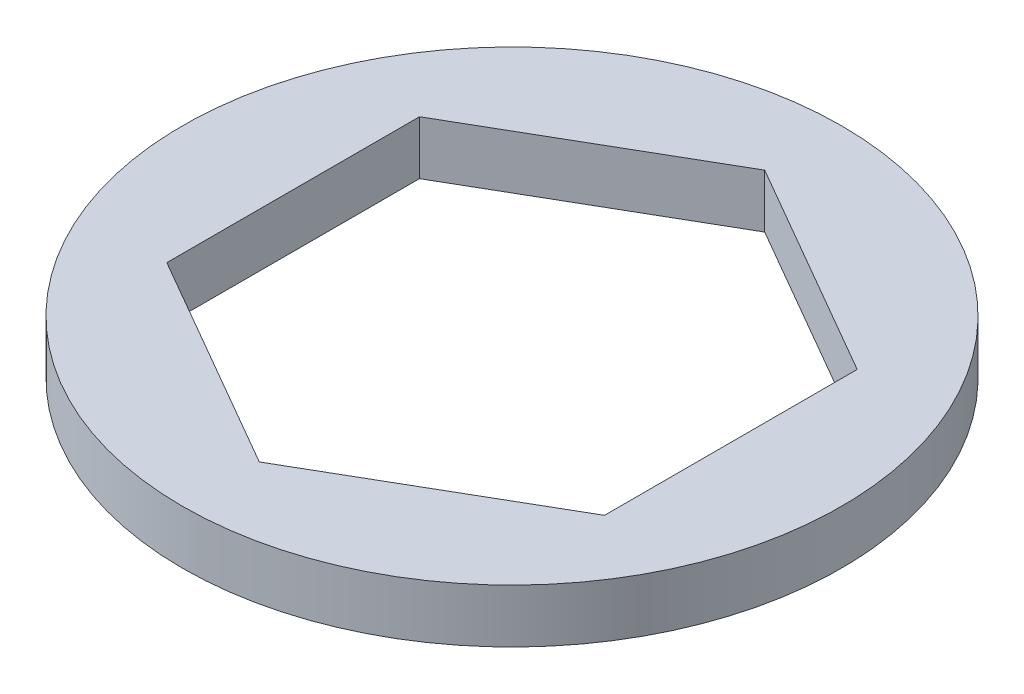
SolidWorks part; units mm, degrees
material "Cast Alloy Steel"
ref_plane "Front Plane" through (0, 0, 0) normal (0, 0, 1) x (1, 0, 0)
ref_plane "Top Plane" through (0, 0, 0) normal (0, 1, 0) x (1, 0, 0)
ref_plane "Right Plane" through (0, 0, 0) normal (1, 0, 0) x (0, 0, -1)
sketch "Sketch1" plane through (0, 0, 0) normal (0, 1, 0) x (1, 0, 0)
  line L0 (0, 0) -> (0, -7.479) construction
  line L1 (0, 7.479) -> (-6.477, 3.7395)
  line L2 (-6.477, 3.7395) -> (-6.477, -3.7395)
  line L3 (-6.477, -3.7395) -> (0, -7.479)
  line L4 (0, -7.479) -> (6.477, -3.7395)
  line L5 (6.477, -3.7395) -> (6.477, 3.7395)
  line L6 (6.477, 3.7395) -> (0, 7.479)
  line L7 (0, 0) -> (6.477, 0) construction
  circle A0 centre (0, 0) radius 6.477 construction
  circle A1 centre (0, 0) radius 9.7536
  dimension "D1" = 12.954
  dimension "D2" = 19.5072
extrude "Boss-Extrude1" add sketch "Sketch1" along normal blind 1.5875
